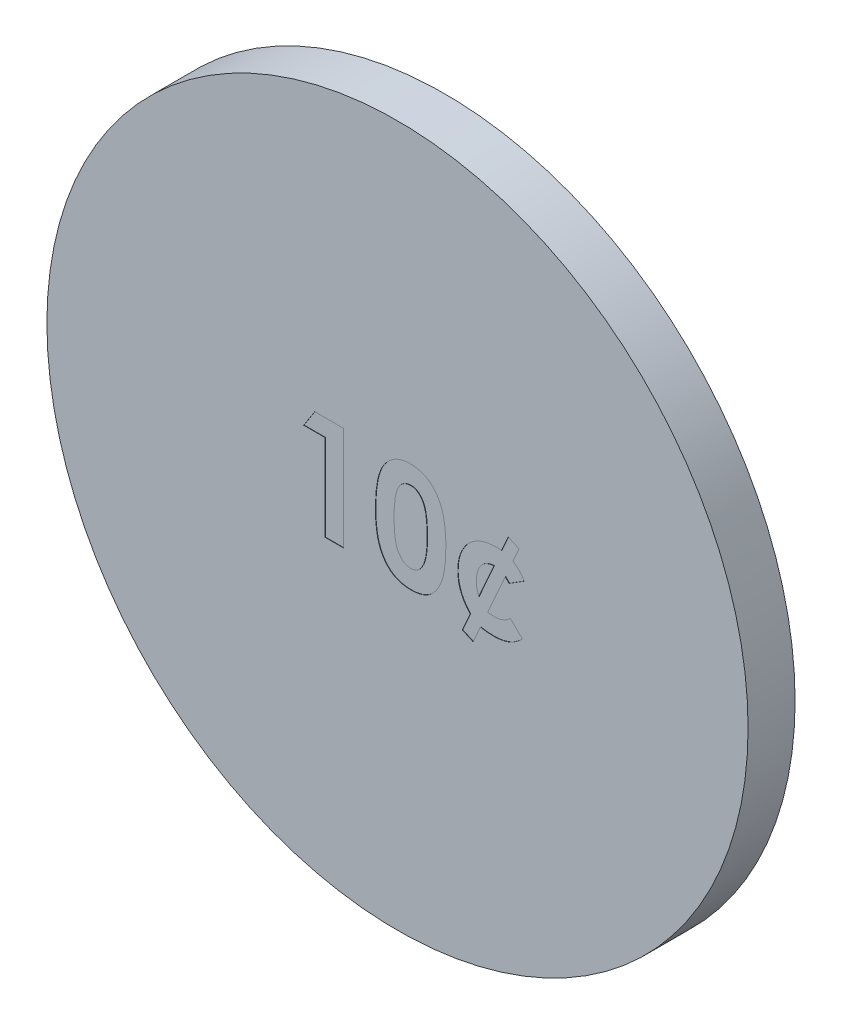
SolidWorks part; units mm, degrees
material "Commercial Bronze, UNS C22000 (90-10 Bronze)"
ref_plane "Front Plane" through (0, 0, 0) normal (0, 0, 1) x (1, 0, 0)
ref_plane "Top Plane" through (0, 0, 0) normal (0, 1, 0) x (1, 0, 0)
ref_plane "Right Plane" through (0, 0, 0) normal (1, 0, 0) x (0, 0, -1)
sketch "Sketch1" plane through (0, 0, 0) normal (0, 0, 1) x (1, 0, 0)
  circle A0 centre (0, 0) radius 8.95
  dimension "D1" = 17.9
extrude "Boss-Extrude1" add sketch "Sketch1" along normal blind 1.2
sketch "Sketch2" plane through (0, 0, 1.2) normal (0, 0, 1) x (1, 0, 0)
  text T0 "<b>10¢</b>" font "Century Gothic" height in points 10
extrude "Cut-Extrude1" cut sketch "Sketch2" against normal blind 0.01
sketch "Sketch3" plane through (0, 0, 1.2) normal (0, 0, 1) x (1, 0, 0)
  text T0 "Dime"
extrude "Cut-Extrude2" [suppressed] cut sketch "Sketch3" against normal blind 0.1
